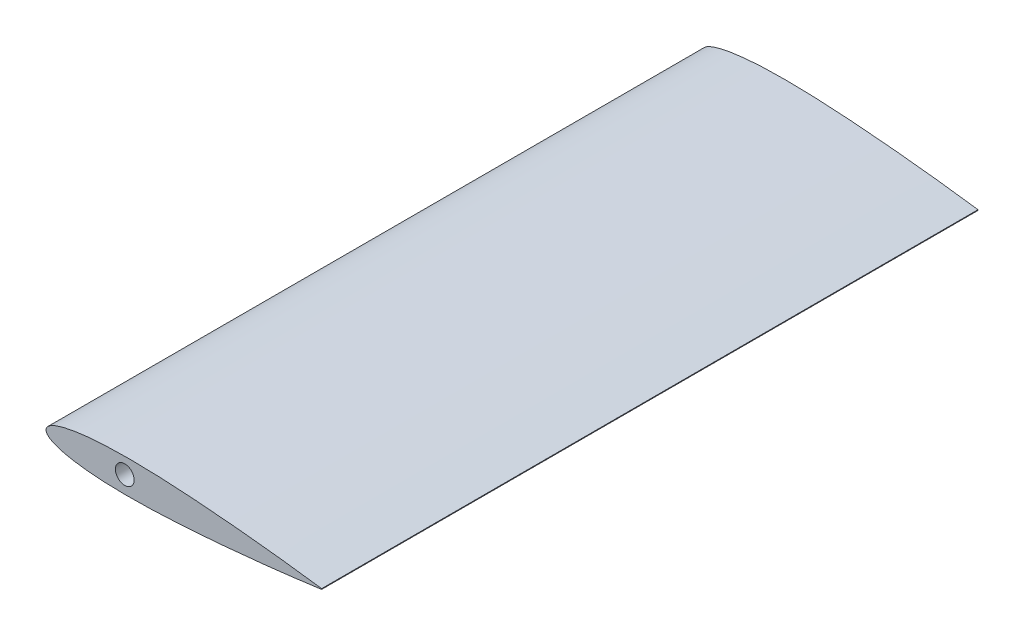
SolidWorks part; units mm, degrees
ref_plane "Front Plane" through (0, 0, 0) normal (0, 0, 1) x (1, 0, 0)
ref_plane "Top Plane" through (0, 0, 0) normal (0, 1, 0) x (1, 0, 0)
ref_plane "Right Plane" through (0, 0, 0) normal (1, 0, 0) x (0, 0, -1)
curve "Curve1"
  spline degree 3 poles (1, 0.0013, 0) (0.9998, 0.0013, 0) (0.999, 0.0014, 0) (0.9973, 0.0016, 0) (0.9944, 0.002, 0) (0.9903, 0.0026, 0) (0.9851, 0.0033, 0) (0.9788, 0.0042, 0) (0.9713, 0.0052, 0) (0.9627, 0.0064, 0) (0.9531, 0.0077, 0) (0.9424, 0.0091, 0) (0.9307, 0.0106, 0) (0.9179, 0.0122, 0) (0.9042, 0.014, 0) (0.8895, 0.0158, 0) (0.874, 0.0177, 0) (0.8575, 0.0196, 0) (0.8402, 0.0217, 0) (0.8222, 0.0237, 0) (0.8033, 0.0259, 0) (0.7838, 0.028, 0) (0.7636, 0.0302, 0) (0.7428, 0.0324, 0) (0.7214, 0.0345, 0) (0.6995, 0.0367, 0) (0.6772, 0.0388, 0) (0.6544, 0.0409, 0) (0.6313, 0.043, 0) (0.6078, 0.045, 0) (0.5841, 0.0469, 0) (0.5602, 0.0488, 0) (0.5362, 0.0505, 0) (0.5121, 0.0522, 0) (0.4879, 0.0537, 0) (0.4638, 0.0551, 0) (0.4398, 0.0563, 0) (0.4159, 0.0574, 0) (0.3922, 0.0583, 0) (0.3688, 0.0591, 0) (0.3456, 0.0596, 0) (0.3228, 0.0599, 0) (0.3005, 0.0601, 0) (0.2786, 0.06, 0) (0.2572, 0.0596, 0) (0.2364, 0.0591, 0) (0.2162, 0.0583, 0) (0.1966, 0.0572, 0) (0.1778, 0.056, 0) (0.1597, 0.0544, 0) (0.1425, 0.0527, 0) (0.126, 0.0507, 0) (0.1104, 0.0486, 0) (0.0958, 0.0462, 0) (0.0821, 0.0436, 0) (0.0693, 0.0408, 0) (0.0576, 0.0378, 0) (0.0468, 0.0347, 0) (0.0372, 0.0313, 0) (0.0286, 0.0279, 0) (0.0211, 0.0243, 0) (0.0147, 0.0206, 0) (0.0094, 0.0167, 0) (0.0053, 0.0128, 0) (0.0023, 0.0087, 0) (0.0004, 0.0044, 0) (-0.0002, 0, 0) (0.0004, -0.0044, 0) (0.0023, -0.0087, 0) (0.0053, -0.0128, 0) (0.0094, -0.0167, 0) (0.0147, -0.0206, 0) (0.0211, -0.0243, 0) (0.0286, -0.0279, 0) (0.0372, -0.0313, 0) (0.0468, -0.0347, 0) (0.0576, -0.0378, 0) (0.0693, -0.0408, 0) (0.0821, -0.0436, 0) (0.0958, -0.0462, 0) (0.1104, -0.0486, 0) (0.126, -0.0507, 0) (0.1425, -0.0527, 0) (0.1597, -0.0544, 0) (0.1778, -0.056, 0) (0.1966, -0.0572, 0) (0.2162, -0.0583, 0) (0.2364, -0.0591, 0) (0.2572, -0.0596, 0) (0.2786, -0.06, 0) (0.3005, -0.0601, 0) (0.3228, -0.0599, 0) (0.3456, -0.0596, 0) (0.3688, -0.0591, 0) (0.3922, -0.0583, 0) (0.4159, -0.0574, 0) (0.4398, -0.0563, 0) (0.4638, -0.0551, 0) (0.4879, -0.0537, 0) (0.5121, -0.0522, 0) (0.5362, -0.0505, 0) (0.5602, -0.0488, 0) (0.5841, -0.0469, 0) (0.6078, -0.045, 0) (0.6313, -0.043, 0) (0.6544, -0.0409, 0) (0.6772, -0.0388, 0) (0.6995, -0.0367, 0) (0.7214, -0.0345, 0) (0.7428, -0.0324, 0) (0.7636, -0.0302, 0) (0.7838, -0.028, 0) (0.8033, -0.0259, 0) (0.8222, -0.0237, 0) (0.8402, -0.0217, 0) (0.8575, -0.0196, 0) (0.874, -0.0177, 0) (0.8895, -0.0158, 0) (0.9042, -0.014, 0) (0.9179, -0.0122, 0) (0.9307, -0.0106, 0) (0.9424, -0.0091, 0) (0.9531, -0.0077, 0) (0.9627, -0.0064, 0) (0.9713, -0.0052, 0) (0.9788, -0.0042, 0) (0.9851, -0.0033, 0) (0.9903, -0.0026, 0) (0.9944, -0.002, 0) (0.9973, -0.0016, 0) (0.999, -0.0014, 0) (0.9998, -0.0013, 0) (1, -0.0013, 0) knots 0 0 0 0 0.000289 0.001156 0.002598 0.004612 0.007194 0.010336 0.014031 0.018272 0.023046 0.028343 0.03415 0.040454 0.047238 0.054489 0.062187 0.070314 0.078852 0.08778 0.097078 0.106722 0.116691 0.126961 0.137507 0.148306 0.159331 0.170556 0.181957 0.193504 0.205171 0.216932 0.228758 0.240621 0.252495 0.26435 0.276161 0.287898 0.299536 0.311047 0.322405 0.333584 0.344559 0.355306 0.3658 0.376018 0.385937 0.395538 0.404798 0.413699 0.422221 0.430349 0.438066 0.445357 0.452209 0.458612 0.464554 0.47003 0.475035 0.479569 0.483637 0.48725 0.490431 0.493219 0.495674 0.497891 0.5 0.502109 0.504326 0.506781 0.509569 0.51275 0.516363 0.520431 0.524965 0.52997 0.535446 0.541388 0.547791 0.554643 0.561934 0.569651 0.577779 0.586301 0.595202 0.604462 0.614063 0.623982 0.6342 0.644694 0.655441 0.666416 0.677595 0.688953 0.700464 0.712102 0.723839 0.73565 0.747505 0.759379 0.771242 0.783068 0.794829 0.806496 0.818043 0.829444 0.840669 0.851694 0.862493 0.873039 0.883309 0.893278 0.902922 0.91222 0.921148 0.929686 0.937813 0.945511 0.952762 0.959546 0.96585 0.971657 0.976954 0.981728 0.985969 0.989664 0.992806 0.995388 0.997402 0.998844 0.999711 1 1 1 1
sketch "Sketch7" plane through (0, 0, 0) normal (0, 0, 1) x (1, 0, 0)
  line L0 (1, -0.1046) -> (1, -0.0305)
  spline S1 degree 3 poles (1, -0.0305) (0.4391, 0.0483) (-1.6744, 0.334) (-4.6175, 0.6842) (-8.1327, 1.0467) (-10.798, 1.2847) (-13.3462, 1.4715) (-15.4585, 1.5943) (-17.5341, 1.6757) (-19.5296, 1.7066) (-21.2181, 1.6828) (-22.5985, 1.6201) (-23.6814, 1.5397) (-24.6714, 1.4322) (-25.4327, 1.3183) (-25.9877, 1.2132) (-26.3625, 1.1311) (-26.7078, 1.0436) (-27.0228, 0.9512) (-27.3068, 0.8541) (-27.5593, 0.7526) (-27.7796, 0.6472) (-27.9675, 0.5378) (-28.1226, 0.4249) (-28.2448, 0.3081) (-28.3336, 0.1871) (-28.3879, 0.0614) (-28.4059, -0.0675) (-28.3879, -0.1965) (-28.3336, -0.3222) (-28.2448, -0.4432) (-28.1226, -0.5599) (-27.9675, -0.6729) (-27.7796, -0.7822) (-27.5593, -0.8877) (-27.3068, -0.9892) (-27.0228, -1.0863) (-26.7078, -1.1787) (-26.3625, -1.2662) (-25.8453, -1.3794) (-25.1286, -1.5039) (-24.1886, -1.6243) (-22.9535, -1.7363) (-21.4032, -1.8152) (-19.2995, -1.8449) (-17.0681, -1.7988) (-14.7563, -1.6926) (-12.6416, -1.5581) (-10.3295, -1.3786) (-8.3035, -1.1944) (-5.6924, -0.9326) (-3.1098, -0.6438) (-0.6443, -0.3306) (0.587, -0.1624) (0.9486, -0.1118) (1, -0.1046) knots 0 0 0 0 0.028343 0.106722 0.148306 0.205171 0.240621 0.276161 0.311047 0.344559 0.376018 0.395538 0.413699 0.430349 0.445357 0.452209 0.458612 0.464554 0.47003 0.475035 0.479569 0.483637 0.48725 0.490431 0.493219 0.495674 0.497891 0.5 0.502109 0.504326 0.506781 0.509569 0.51275 0.516363 0.520431 0.524965 0.52997 0.535446 0.541388 0.547791 0.561934 0.577779 0.595202 0.623982 0.655441 0.700464 0.73565 0.771242 0.806496 0.851694 0.873039 0.937813 0.981728 0.997402 1 1 1 1
extrude "Boss-Extrude4" add sketch "Sketch7" along normal blind 70
sketch "Sketch8" plane through (0, 0, 70) normal (0, 0, 1) x (1, 0, 0)
  line L0 (1, -0.1046) -> (1, -0.0305) construction
  circle A0 centre (-20, 0) radius 1
  dimension "D1" = 21
extrude "Cut-Extrude3" cut sketch "Sketch8" against normal through all
